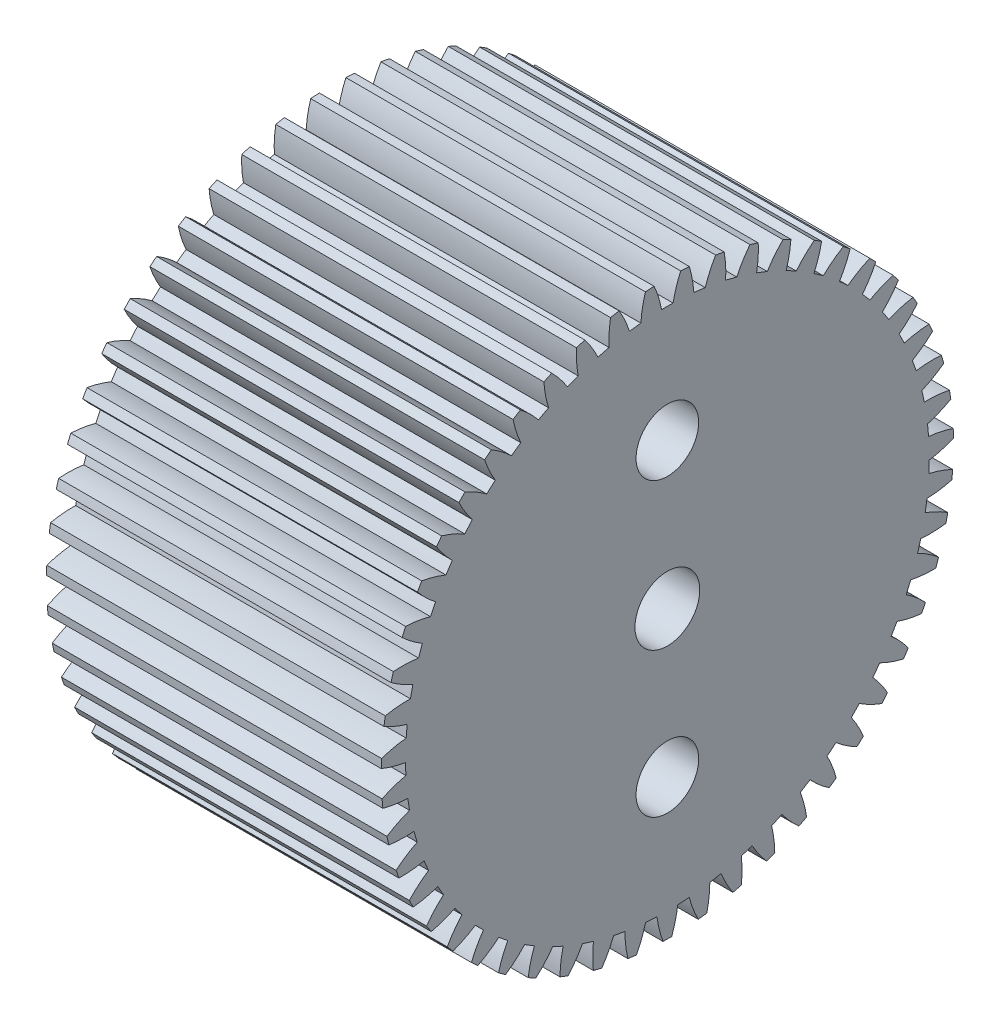
SolidWorks part; units mm, degrees
ref_plane "Plane1" through (0, 0, 0) normal (0, 0, 1) x (1, 0, 0)
ref_plane "Plane2" through (0, 0, 0) normal (0, 1, 0) x (1, 0, 0)
ref_plane "Plane3" through (0, 0, 0) normal (1, 0, 0) x (0, 0, -1)
sketch "HoldingSke" plane through (0, 0, 0) normal (0, 1, 0) x (1, 0, 0)
  line L0 (0, 0) -> (1.2586, -1.5543)
  line L1 (-15, 0) -> (100, 0) construction
  line L2 (0, 0) -> (-2.1039, 2.3779)
  line L3 (0, 0) -> (-11.863, 4.5341)
  line L4 (0, 0) -> (5.4348, 6.7114)
  line L5 (0, 0) -> (-46.8476, -17.4728)
  line L6 (0, 0) -> (-6.6317, -4.4744)
  line L7 (-2.1039, 2.3779) -> (8.6586, 51.2059)
  line L8 (-76.2, 54.61) -> (-75.7, 54.61)
  line L9 (-67.7845, 28.3722) -> (-49.3413, 33.142)
  line L10 (-76.2, 71.12) -> (104.1128, 71.12)
  line L11 (0, 0) -> (-8, 0)
  line L12 (-76.2, 101.6) -> (-76.181, 101.6)
  line L13 (24.9733, 27.94) -> (52.9518, 28.4284)
  line L14 (24.9733, 27.94) -> (24.9743, 27.94)
  line L15 (24.9733, 27.94) -> (100.4006, 29.5858)
  line L16 (-63.627, -0.5) -> (-12.827, -0.5)
  circle A0 centre (0, 0) radius 1.5
  circle A1 centre (0, 0) radius 12.124
  circle A2 centre (0, 0) radius 37.5
  circle A3 centre (0, 0) radius 1.5
  dimension "MHD" = 24.248
  dimension "Hub_dia" = 75
  dimension "Bore" = 3
  dimension "MBD" = 3
  dimension "Num_teeth" = 51
  dimension "Pitch" = 2
  dimension "Overall_len" = 50
  dimension "Show_teeth" = 51
  dimension "Thickness" = 8
  dimension "OAL" = 50.0001
  dimension "T_dim" = 0.5
  dimension "Ap" = 14.5
  dimension "H" = 19.05
  dimension "Pitch_radius" = 180.3128
  dimension "Width" = 8
  dimension "Backlash" = 0.019
  dimension "Addendum_fac" = 1
  dimension "Dedendum_fac" = 1.25
  dimension "Clearance_fac" = 0.25
  dimension "Dedendum_add" = 0.001
  dimension "Module" = 0.5
sketch "BasProSke" plane through (0, 0, 0) normal (0, 1, 0) x (1, 0, 0)
  line L0 (-10, 0) -> (60, 0) construction
  line L1 (0, 0) -> (0, 13.25)
  line L2 (0, 0) -> (8, 0)
  line L3 (8, 0) -> (8, 13.25)
  line L4 (8, 13.25) -> (0, 13.25)
  dimension "Thickness" = 8
  dimension "Diameter" = 26.5
revolve "Base-Revolve" add sketch "BasProSke" angle 360 about L0
sketch "TooCutSke" plane through (0, 0, 0) normal (1, 0, 0) x (0, 0, -1)
  line L1 (0, 0) -> (0, 107) construction
  line L2 (0, 0) -> (-0.4259, 12.7429) construction
  line L3 (0, 0) -> (-1.5692, 25.4415) construction
  line L4 (-0.4259, 12.7429) -> (-0.7846, 12.7208) construction
  arc A0 (0.2655, 12.1211) -> (-0.2655, 12.1211) centre (0, 0) ccw
  arc A1 (0.6267, 13.2606) -> (-0.6267, 13.2606) centre (0, 0) ccw
  circle A2 centre (0, 0) radius 12.75 construction
  circle A3 centre (0, 0) radius 12.3439 construction
  arc A4 (-0.2655, 12.1211) -> (-0.6267, 13.2606) centre (-5.2742, 11.1604) ccw
  arc A5 (0.6267, 13.2606) -> (0.2655, 12.1211) centre (5.2742, 11.1604) ccw
  dimension "Root_dia" = 24.248
  dimension "Overcut_dia" = 26.5508
  dimension "Pitch_dia" = 25.5
  dimension "Base_dia" = 24.6878
  dimension "Flank_rad" = 5.1
  dimension "Half_ang" = 3.529
  dimension "Half_CT" = 0.3594
extrude "ToothCut" cut sketch "TooCutSke" along normal through all
fillet "Breaks" [suppressed] radius 0.01
fillet "RootFillets" [suppressed] radius 0.126
pattern_circular "TeethCuts" count 51 every 7.059 about axis through (-10, 0, 0) along (1, 0, 0) of "ToothCut", "RootFillets", "Breaks"
sketch "HubNeaOneSke" plane through (0, 0, 0) normal (-1, 0, 0) x (0, 0, 1)
  circle A0 centre (0, 0) radius 12.124
  dimension "Diameter" = 24.248
extrude "HubNearOne" [suppressed] add sketch "HubNeaOneSke" along normal blind 42.0001
sketch "HubNeaBotSke" plane through (0, 0, 0) normal (-1, 0, 0) x (0, 0, 1)
  circle A0 centre (0, 0) radius 12.124
  dimension "Diameter" = 24.248
extrude "HubNearBoth" [suppressed] add sketch "HubNeaBotSke" along normal blind 21
ref_plane "FarPln" through (8, 0, 0) normal (1, 0, 0) x (0, 0, -1)
sketch "HubFarSke" plane through (8, 0, 0) normal (1, 0, 0) x (0, 0, -1)
  circle A0 centre (0, 0) radius 12.124
  dimension "Diameter" = 24.248
extrude "HubFar" [suppressed] add sketch "HubFarSke" along normal blind 21
sketch "BorSke" plane through (0, 0, 0) normal (1, 0, 0) x (0, 0, -1)
  circle A0 centre (0, 0) radius 1.5
  dimension "Diameter" = 3
extrude "Bore" cut sketch "BorSke" along normal mid plane 100.0001
sketch "KeySke" plane through (0, 0, 0) normal (1, 0, 0) x (0, 0, -1)
  line L0 (-0.6, 0) -> (-0.6, 2)
  line L1 (-0.6, 2) -> (0.6, 2)
  line L2 (0.6, 2) -> (0.6, 0)
  line L3 (0, 0) -> (0, 34) construction
  line L4 (-0.6, 0) -> (0.6, 0)
  dimension "Offset" = 2
  dimension "Width" = 1.2
extrude "Keyway" [suppressed] cut sketch "KeySke" along normal mid plane 100.0001
pattern_circular "Keyway2" [suppressed] count 2 every 90 about axis through (-10, 0, 0) along (1, 0, 0)
sketch "草圖1" plane through (8, 0, 0) normal (1, 0, 0) x (0, 0, -1)
  circle A0 centre (0, 0) radius 6.75 construction
  circle A1 centre (0, 6.75) radius 1.45
  circle A2 centre (0, -6.75) radius 1.45
  dimension "D1" = 13.5
  dimension "D2" = 2.9
extrude "除料-伸長1" cut sketch "草圖1" against normal up to next
sketch "草圖2" plane through (0, 0, 0) normal (-1, 0, 0) x (0, 0, 1)
  circle A0 centre (0, 6.75) radius 1.45 construction
  circle A1 centre (0, 6.75) radius 1.45
  circle A2 centre (0, 0) radius 1.5 construction
  circle A3 centre (0, 0) radius 1.5
  circle A4 centre (0, -6.75) radius 1.45 construction
  circle A5 centre (0, -6.75) radius 1.45
  arc A204 (12.1235, -0.1079) -> (13.2484, 0.2076) centre (11.3175, 4.928) ccw
  arc A205 (13.2484, 0.2076) -> (13.236, 0.6084) centre (0, 0) ccw
  arc A206 (13.236, 0.6084) -> (12.0939, 0.8541) centre (11.5994, -4.2219) ccw
  arc A207 (12.0939, 0.8541) -> (12.0449, 1.3827) centre (0, 0) ccw
  arc A208 (12.0449, 1.3827) -> (13.1224, 1.8341) centre (10.6262, 6.2814) ccw
  arc A209 (13.1224, 1.8341) -> (13.0609, 2.2303) centre (0, 0) ccw
  arc A210 (13.0609, 2.2303) -> (11.8973, 2.3338) centre (12.0303, -2.7645) ccw
  arc A211 (11.8973, 2.3338) -> (11.7837, 2.8524) centre (0, 0) ccw
  arc A212 (11.7837, 2.8524) -> (12.7976, 3.4328) centre (9.7737, 7.5396) ccw
  arc A213 (12.7976, 3.4328) -> (12.6879, 3.8184) centre (0, 0) ccw
  arc A214 (12.6879, 3.8184) -> (11.5203, 3.7781) centre (12.2789, -1.2651) ccw
  arc A215 (11.5203, 3.7781) -> (11.3438, 4.2789) centre (0, 0) ccw
  arc A216 (11.3438, 4.2789) -> (12.2787, 4.9795) centre (8.7731, 8.6836) ccw
  arc A217 (12.2787, 4.9795) -> (12.1225, 5.3487) centre (0, 0) ccw
  arc A218 (12.1225, 5.3487) -> (10.9687, 5.1652) centre (12.3413, 0.2534) ccw
  arc A219 (10.9687, 5.1652) -> (10.732, 5.6405) centre (0, 0) ccw
  arc A220 (10.732, 5.6405) -> (11.5738, 6.4506) centre (7.6395, 9.6959) ccw
  arc A221 (11.5738, 6.4506) -> (11.3733, 6.7979) centre (0, 0) ccw
  arc A222 (11.3733, 6.7979) -> (10.2508, 6.474) centre (12.2166, 1.7681) ccw
  arc A223 (10.2508, 6.474) -> (9.9575, 6.9166) centre (0, 0) ccw
  arc A224 (9.9575, 6.9166) -> (10.6933, 7.824) centre (6.3901, 10.5612) ccw
  arc A225 (10.6933, 7.824) -> (10.4517, 8.144) centre (0, 0) ccw
  arc A226 (10.4517, 8.144) -> (9.3775, 7.6846) centre (11.9067, 3.2559) ccw
  arc A227 (9.3775, 7.6846) -> (9.0321, 8.0878) centre (0, 0) ccw
  arc A228 (9.0321, 8.0878) -> (9.6508, 9.0788) centre (5.0438, 11.2664) ccw
  arc A229 (9.6508, 9.0788) -> (9.3717, 9.3666) centre (0, 0) ccw
  arc A230 (9.3717, 9.3666) -> (8.3621, 8.7788) centre (11.4164, 4.6945) ccw
  arc A231 (8.3621, 8.7788) -> (7.9698, 9.1364) centre (0, 0) ccw
  arc A232 (7.9698, 9.1364) -> (8.462, 10.196) centre (3.6211, 11.8008) ccw
  arc A233 (8.462, 10.196) -> (8.1496, 10.4473) centre (0, 0) ccw
  arc A234 (8.1496, 10.4473) -> (7.2199, 9.7398) centre (10.7529, 6.0618) ccw
  arc A235 (7.2199, 9.7398) -> (6.7866, 10.0466) centre (0, 0) ccw
  arc A236 (6.7866, 10.0466) -> (7.1449, 11.1586) centre (2.1434, 12.1564) ccw
  arc A237 (7.1449, 11.1586) -> (6.804, 11.3696) centre (0, 0) ccw
  arc A238 (6.804, 11.3696) -> (5.9683, 10.5532) centre (9.9265, 7.3373) ccw
  arc A239 (5.9683, 10.5532) -> (5.5005, 10.8044) centre (0, 0) ccw
  arc A240 (5.5005, 10.8044) -> (5.7195, 11.952) centre (0.6333, 12.3276) ccw
  arc A241 (5.7195, 11.952) -> (5.3552, 12.1196) centre (0, 0) ccw
  arc A242 (5.3552, 12.1196) -> (4.6262, 11.2067) centre (8.9496, 8.5015) ccw
  arc A243 (4.6262, 11.2067) -> (4.1311, 11.3985) centre (0, 0) ccw
  arc A244 (4.1311, 11.3985) -> (4.2074, 12.5643) centre (-0.8864, 12.312) ccw
  arc A245 (4.2074, 12.5643) -> (3.8253, 12.6858) centre (0, 0) ccw
  arc A246 (3.8253, 12.6858) -> (3.2139, 11.6903) centre (7.837, 9.5369) ccw
  arc A247 (3.2139, 11.6903) -> (2.6991, 11.8197) centre (0, 0) ccw
  arc A248 (2.6991, 11.8197) -> (2.6315, 12.9861) centre (-2.3927, 12.1098) ccw
  arc A249 (2.6315, 12.9861) -> (2.2373, 13.0597) centre (0, 0) ccw
  arc A250 (2.2373, 13.0597) -> (1.753, 11.9966) centre (6.6057, 10.4277) ccw
  arc A251 (1.753, 11.9966) -> (1.2261, 12.0618) centre (0, 0) ccw
  arc A252 (1.2261, 12.0618) -> (1.0157, 13.211) centre (-3.8627, 11.7239) ccw
  arc A253 (1.0157, 13.211) -> (0.6155, 13.2357) centre (0, 0) ccw
  arc A254 (0.6155, 13.2357) -> (0.2655, 12.1211) centre (5.2742, 11.1604) ccw
  arc A255 (0.2655, 12.1211) -> (-0.2655, 12.1211) centre (0, 0) ccw
  arc A256 (-0.2655, 12.1211) -> (-0.6155, 13.2357) centre (-5.2742, 11.1604) ccw
  arc A257 (-0.6155, 13.2357) -> (-1.0157, 13.211) centre (0, 0) ccw
  arc A258 (-1.0157, 13.211) -> (-1.2261, 12.0618) centre (3.8627, 11.7239) ccw
  arc A259 (-1.2261, 12.0618) -> (-1.753, 11.9966) centre (0, 0) ccw
  arc A260 (-1.753, 11.9966) -> (-2.2373, 13.0597) centre (-6.6057, 10.4277) ccw
  arc A261 (-2.2373, 13.0597) -> (-2.6315, 12.9861) centre (0, 0) ccw
  arc A262 (-2.6315, 12.9861) -> (-2.6991, 11.8197) centre (2.3927, 12.1098) ccw
  arc A263 (-2.6991, 11.8197) -> (-3.2139, 11.6903) centre (0, 0) ccw
  arc A264 (-3.2139, 11.6903) -> (-3.8253, 12.6858) centre (-7.837, 9.5369) ccw
  arc A265 (-3.8253, 12.6858) -> (-4.2074, 12.5643) centre (0, 0) ccw
  arc A266 (-4.2074, 12.5643) -> (-4.1311, 11.3985) centre (0.8864, 12.312) ccw
  arc A267 (-4.1311, 11.3985) -> (-4.6262, 11.2067) centre (0, 0) ccw
  arc A268 (-4.6262, 11.2067) -> (-5.3552, 12.1196) centre (-8.9496, 8.5015) ccw
  arc A269 (-5.3552, 12.1196) -> (-5.7195, 11.952) centre (0, 0) ccw
  arc A270 (-5.7195, 11.952) -> (-5.5005, 10.8044) centre (-0.6333, 12.3276) ccw
  arc A271 (-5.5005, 10.8044) -> (-5.9683, 10.5532) centre (0, 0) ccw
  arc A272 (-5.9683, 10.5532) -> (-6.804, 11.3696) centre (-9.9265, 7.3373) ccw
  arc A273 (-6.804, 11.3696) -> (-7.1449, 11.1586) centre (0, 0) ccw
  arc A274 (-7.1449, 11.1586) -> (-6.7866, 10.0466) centre (-2.1434, 12.1564) ccw
  arc A275 (-6.7866, 10.0466) -> (-7.2199, 9.7398) centre (0, 0) ccw
  arc A276 (-7.2199, 9.7398) -> (-8.1496, 10.4473) centre (-10.7529, 6.0618) ccw
  arc A277 (-8.1496, 10.4473) -> (-8.462, 10.196) centre (0, 0) ccw
  arc A278 (-8.462, 10.196) -> (-7.9698, 9.1364) centre (-3.6211, 11.8008) ccw
  arc A279 (-7.9698, 9.1364) -> (-8.3621, 8.7788) centre (0, 0) ccw
  arc A280 (-8.3621, 8.7788) -> (-9.3717, 9.3666) centre (-11.4164, 4.6945) ccw
  arc A281 (-9.3717, 9.3666) -> (-9.6508, 9.0788) centre (0, 0) ccw
  arc A282 (-9.6508, 9.0788) -> (-9.0321, 8.0878) centre (-5.0438, 11.2664) ccw
  arc A283 (-9.0321, 8.0878) -> (-9.3775, 7.6846) centre (0, 0) ccw
  arc A284 (-9.3775, 7.6846) -> (-10.4517, 8.144) centre (-11.9067, 3.2559) ccw
  arc A285 (-10.4517, 8.144) -> (-10.6933, 7.824) centre (0, 0) ccw
  arc A286 (-10.6933, 7.824) -> (-9.9575, 6.9166) centre (-6.3901, 10.5612) ccw
  arc A287 (-9.9575, 6.9166) -> (-10.2508, 6.474) centre (0, 0) ccw
  arc A288 (-10.2508, 6.474) -> (-11.3733, 6.7979) centre (-12.2166, 1.7681) ccw
  arc A289 (-11.3733, 6.7979) -> (-11.5738, 6.4506) centre (0, 0) ccw
  arc A290 (-11.5738, 6.4506) -> (-10.732, 5.6405) centre (-7.6395, 9.6959) ccw
  arc A291 (-10.732, 5.6405) -> (-10.9687, 5.1652) centre (0, 0) ccw
  arc A292 (-10.9687, 5.1652) -> (-12.1225, 5.3487) centre (-12.3413, 0.2534) ccw
  arc A293 (-12.1225, 5.3487) -> (-12.2787, 4.9795) centre (0, 0) ccw
  arc A294 (-12.2787, 4.9795) -> (-11.3438, 4.2789) centre (-8.7731, 8.6836) ccw
  arc A295 (-11.3438, 4.2789) -> (-11.5203, 3.7781) centre (0, 0) ccw
  arc A296 (-11.5203, 3.7781) -> (-12.6879, 3.8184) centre (-12.2789, -1.2651) ccw
  arc A297 (-12.6879, 3.8184) -> (-12.7976, 3.4328) centre (0, 0) ccw
  arc A298 (-12.7976, 3.4328) -> (-11.7837, 2.8524) centre (-9.7737, 7.5396) ccw
  arc A299 (-11.7837, 2.8524) -> (-11.8973, 2.3338) centre (0, 0) ccw
  arc A300 (-11.8973, 2.3338) -> (-13.0609, 2.2303) centre (-12.0303, -2.7645) ccw
  arc A301 (-13.0609, 2.2303) -> (-13.1224, 1.8341) centre (0, 0) ccw
  arc A302 (-13.1224, 1.8341) -> (-12.0449, 1.3827) centre (-10.6262, 6.2814) ccw
  arc A303 (-12.0449, 1.3827) -> (-12.0939, 0.8541) centre (0, 0) ccw
  arc A304 (-12.0939, 0.8541) -> (-13.236, 0.6084) centre (-11.5994, -4.2219) ccw
  arc A305 (-13.236, 0.6084) -> (-13.2484, 0.2076) centre (0, 0) ccw
  arc A306 (-13.2484, 0.2076) -> (-12.1235, -0.1079) centre (-11.3175, 4.928) ccw
  arc A307 (-12.1235, -0.1079) -> (-12.1072, -0.6386) centre (0, 0) ccw
  arc A308 (-12.1072, -0.6386) -> (-13.2105, -1.0228) centre (-10.9927, -5.6153) ccw
  arc A309 (-13.2105, -1.0228) -> (-13.1735, -1.422) centre (0, 0) ccw
  arc A310 (-13.1735, -1.422) -> (-12.0184, -1.597) centre (-11.8373, 3.4998) ccw
  arc A311 (-12.0184, -1.597) -> (-11.9369, -2.1216) centre (0, 0) ccw
  arc A312 (-11.9369, -2.1216) -> (-12.9846, -2.6385) centre (-10.2193, -6.9237) ccw
  arc A313 (-12.9846, -2.6385) -> (-12.8989, -3.0301) centre (0, 0) ccw
  arc A314 (-12.8989, -3.0301) -> (-11.731, -3.0618) centre (-12.1777, 2.0186) ccw
  arc A315 (-11.731, -3.0618) -> (-11.5857, -3.5724) centre (0, 0) ccw
  arc A316 (-11.5857, -3.5724) -> (-12.562, -4.2141) centre (-9.291, -8.127) ccw
  arc A317 (-12.562, -4.2141) -> (-12.4287, -4.5923) centre (0, 0) ccw
  arc A318 (-12.4287, -4.5923) -> (-11.2659, -4.4802) centre (-12.3335, 0.5068) ccw
  arc A319 (-11.2659, -4.4802) -> (-11.0589, -4.9691) centre (0, 0) ccw
  arc A320 (-11.0589, -4.9691) -> (-11.9489, -5.7259) centre (-8.2219, -9.2072) ccw
  arc A321 (-11.9489, -5.7259) -> (-11.7702, -6.0848) centre (0, 0) ccw
  arc A322 (-11.7702, -6.0848) -> (-10.6299, -5.8307) centre (-12.3023, -1.0126) ccw
  arc A323 (-10.6299, -5.8307) -> (-10.3644, -6.2904) centre (0, 0) ccw
  arc A324 (-10.3644, -6.2904) -> (-11.1547, -7.1509) centre (-7.0281, -10.1478) ccw
  arc A325 (-11.1547, -7.1509) -> (-10.9332, -7.4851) centre (0, 0) ccw
  arc A326 (-10.9332, -7.4851) -> (-9.8328, -7.0928) centre (-12.0846, -2.5168) ccw
  arc A327 (-9.8328, -7.0928) -> (-9.5129, -7.5164) centre (0, 0) ccw
  arc A328 (-9.5129, -7.5164) -> (-10.1914, -8.4675) centre (-5.7278, -10.9345) ccw
  arc A329 (-10.1914, -8.4675) -> (-9.9305, -8.7719) centre (0, 0) ccw
  arc A330 (-9.9305, -8.7719) -> (-8.8867, -8.2473) centre (-11.6837, -3.9828) ccw
  arc A331 (-8.8867, -8.2473) -> (-8.5171, -8.6285) centre (0, 0) ccw
  arc A332 (-8.5171, -8.6285) -> (-9.0736, -9.6557) centre (-4.3407, -11.5555) ccw
  arc A333 (-9.0736, -9.6557) -> (-8.7773, -9.9258) centre (0, 0) ccw
  arc A334 (-8.7773, -9.9258) -> (-7.8058, -9.2769) centre (-11.1057, -5.3884) ccw
  arc A335 (-7.8058, -9.2769) -> (-7.3922, -9.6097) centre (0, 0) ccw
  arc A336 (-7.3922, -9.6097) -> (-7.8183, -10.6975) centre (-2.8877, -12.0014) ccw
  arc A337 (-7.8183, -10.6975) -> (-7.491, -10.9292) centre (0, 0) ccw
  arc A338 (-7.491, -10.9292) -> (-6.6066, -10.1658) centre (-10.3594, -6.7123) ccw
  arc A339 (-6.6066, -10.1658) -> (-6.1552, -10.4453) centre (0, 0) ccw
  arc A340 (-6.1552, -10.4453) -> (-6.4444, -11.5772) centre (-1.391, -12.2653) ccw
  arc A341 (-6.4444, -11.5772) -> (-6.0911, -11.7669) centre (0, 0) ccw
  arc A342 (-6.0911, -11.7669) -> (-5.3073, -10.9006) centre (-9.456, -7.9345) ccw
  arc A343 (-5.3073, -10.9006) -> (-4.825, -11.1225) centre (0, 0) ccw
  arc A344 (-4.825, -11.1225) -> (-4.9728, -12.2814) centre (0.1268, -12.3432) ccw
  arc A345 (-4.9728, -12.2814) -> (-4.599, -12.4263) centre (0, 0) ccw
  arc A346 (-4.599, -12.4263) -> (-3.9275, -11.4702) centre (-8.4093, -9.0363) ccw
  arc A347 (-3.9275, -11.4702) -> (-3.4216, -11.6312) centre (0, 0) ccw
  arc A348 (-3.4216, -11.6312) -> (-3.4259, -12.7994) centre (1.6427, -12.2341) ccw
  arc A349 (-3.4259, -12.7994) -> (-3.0371, -12.8972) centre (0, 0) ccw
  arc A350 (-3.0371, -12.8972) -> (-2.4882, -11.8659) centre (-7.2351, -10.0013) ccw
  arc A351 (-2.4882, -11.8659) -> (-1.9663, -11.9635) centre (0, 0) ccw
  arc A352 (-1.9663, -11.9635) -> (-1.827, -13.1234) centre (3.1336, -11.9395) ccw
  arc A353 (-1.827, -13.1234) -> (-1.4291, -13.1727) centre (0, 0) ccw
  arc A354 (-1.4291, -13.1727) -> (-1.0111, -12.0818) centre (-5.9512, -10.8146) ccw
  arc A355 (-1.0111, -12.0818) -> (-0.4812, -12.1144) centre (0, 0) ccw
  arc A356 (-0.4812, -12.1144) -> (-0.2005, -13.2485) centre (4.5771, -11.4639) ccw
  arc A357 (-0.2005, -13.2485) -> (0.2005, -13.2485) centre (0, 0) ccw
  arc A358 (0.2005, -13.2485) -> (0.4812, -12.1144) centre (-4.5771, -11.4639) ccw
  arc A359 (0.4812, -12.1144) -> (1.0111, -12.0818) centre (0, 0) ccw
  arc A360 (1.0111, -12.0818) -> (1.4291, -13.1727) centre (5.9512, -10.8146) ccw
  arc A361 (1.4291, -13.1727) -> (1.827, -13.1234) centre (0, 0) ccw
  arc A362 (1.827, -13.1234) -> (1.9663, -11.9635) centre (-3.1336, -11.9395) ccw
  arc A363 (1.9663, -11.9635) -> (2.4882, -11.8659) centre (0, 0) ccw
  arc A364 (2.4882, -11.8659) -> (3.0371, -12.8972) centre (7.2351, -10.0013) ccw
  arc A365 (3.0371, -12.8972) -> (3.4259, -12.7994) centre (0, 0) ccw
  arc A366 (3.4259, -12.7994) -> (3.4216, -11.6312) centre (-1.6427, -12.2341) ccw
  arc A367 (3.4216, -11.6312) -> (3.9275, -11.4702) centre (0, 0) ccw
  arc A368 (3.9275, -11.4702) -> (4.599, -12.4263) centre (8.4093, -9.0363) ccw
  arc A369 (4.599, -12.4263) -> (4.9728, -12.2814) centre (0, 0) ccw
  arc A370 (4.9728, -12.2814) -> (4.825, -11.1225) centre (-0.1268, -12.3432) ccw
  arc A371 (4.825, -11.1225) -> (5.3073, -10.9006) centre (0, 0) ccw
  arc A372 (5.3073, -10.9006) -> (6.0911, -11.7669) centre (9.456, -7.9345) ccw
  arc A373 (6.0911, -11.7669) -> (6.4444, -11.5772) centre (0, 0) ccw
  arc A374 (6.4444, -11.5772) -> (6.1552, -10.4453) centre (1.391, -12.2653) ccw
  arc A375 (6.1552, -10.4453) -> (6.6066, -10.1658) centre (0, 0) ccw
  arc A376 (6.6066, -10.1658) -> (7.491, -10.9292) centre (10.3594, -6.7123) ccw
  arc A377 (7.491, -10.9292) -> (7.8183, -10.6975) centre (0, 0) ccw
  arc A378 (7.8183, -10.6975) -> (7.3922, -9.6097) centre (2.8877, -12.0014) ccw
  arc A379 (7.3922, -9.6097) -> (7.8058, -9.2769) centre (0, 0) ccw
  arc A380 (7.8058, -9.2769) -> (8.7773, -9.9258) centre (11.1057, -5.3884) ccw
  arc A381 (8.7773, -9.9258) -> (9.0736, -9.6557) centre (0, 0) ccw
  arc A382 (9.0736, -9.6557) -> (8.5171, -8.6285) centre (4.3407, -11.5555) ccw
  arc A383 (8.5171, -8.6285) -> (8.8867, -8.2473) centre (0, 0) ccw
  arc A384 (8.8867, -8.2473) -> (9.9305, -8.7719) centre (11.6837, -3.9828) ccw
  arc A385 (9.9305, -8.7719) -> (10.1914, -8.4675) centre (0, 0) ccw
  arc A386 (10.1914, -8.4675) -> (9.5129, -7.5164) centre (5.7278, -10.9345) ccw
  arc A387 (9.5129, -7.5164) -> (9.8328, -7.0928) centre (0, 0) ccw
  arc A388 (9.8328, -7.0928) -> (10.9332, -7.4851) centre (12.0846, -2.5168) ccw
  arc A389 (10.9332, -7.4851) -> (11.1547, -7.1509) centre (0, 0) ccw
  arc A390 (11.1547, -7.1509) -> (10.3644, -6.2904) centre (7.0281, -10.1478) ccw
  arc A391 (10.3644, -6.2904) -> (10.6299, -5.8307) centre (0, 0) ccw
  arc A392 (10.6299, -5.8307) -> (11.7702, -6.0848) centre (12.3023, -1.0126) ccw
  arc A393 (11.7702, -6.0848) -> (11.9489, -5.7259) centre (0, 0) ccw
  arc A394 (11.9489, -5.7259) -> (11.0589, -4.9691) centre (8.2219, -9.2072) ccw
  arc A395 (11.0589, -4.9691) -> (11.2659, -4.4802) centre (0, 0) ccw
  arc A396 (11.2659, -4.4802) -> (12.4287, -4.5923) centre (12.3335, 0.5068) ccw
  arc A397 (12.4287, -4.5923) -> (12.562, -4.2141) centre (0, 0) ccw
  arc A398 (12.562, -4.2141) -> (11.5857, -3.5724) centre (9.291, -8.127) ccw
  arc A399 (11.5857, -3.5724) -> (11.731, -3.0618) centre (0, 0) ccw
  arc A400 (11.731, -3.0618) -> (12.8989, -3.0301) centre (12.1777, 2.0186) ccw
  arc A401 (12.8989, -3.0301) -> (12.9846, -2.6385) centre (0, 0) ccw
  arc A402 (12.9846, -2.6385) -> (11.9369, -2.1216) centre (10.2193, -6.9237) ccw
  arc A403 (11.9369, -2.1216) -> (12.0184, -1.597) centre (0, 0) ccw
  arc A404 (12.0184, -1.597) -> (13.1735, -1.422) centre (11.8373, 3.4998) ccw
  arc A405 (13.1735, -1.422) -> (13.2105, -1.0228) centre (0, 0) ccw
  arc A406 (13.2105, -1.0228) -> (12.1072, -0.6386) centre (10.9927, -5.6153) ccw
  arc A407 (12.1072, -0.6386) -> (12.1235, -0.1079) centre (0, 0) ccw
  arc A408 (12.1235, -0.1079) -> (13.2484, 0.2076) centre (11.3175, 4.928) ccw
  arc A409 (13.2484, 0.2076) -> (13.236, 0.6084) centre (0, 0) ccw
  arc A410 (13.236, 0.6084) -> (12.0939, 0.8541) centre (11.5994, -4.2219) ccw
  arc A411 (12.0939, 0.8541) -> (12.0449, 1.3827) centre (0, 0) ccw
  arc A412 (12.0449, 1.3827) -> (13.1224, 1.8341) centre (10.6262, 6.2814) ccw
  arc A413 (13.1224, 1.8341) -> (13.0609, 2.2303) centre (0, 0) ccw
  arc A414 (13.0609, 2.2303) -> (11.8973, 2.3338) centre (12.0303, -2.7645) ccw
  arc A415 (11.8973, 2.3338) -> (11.7837, 2.8524) centre (0, 0) ccw
  arc A416 (11.7837, 2.8524) -> (12.7976, 3.4328) centre (9.7737, 7.5396) ccw
  arc A417 (12.7976, 3.4328) -> (12.6879, 3.8184) centre (0, 0) ccw
  arc A418 (12.6879, 3.8184) -> (11.5203, 3.7781) centre (12.2789, -1.2651) ccw
  arc A419 (11.5203, 3.7781) -> (11.3438, 4.2789) centre (0, 0) ccw
  arc A420 (11.3438, 4.2789) -> (12.2787, 4.9795) centre (8.7731, 8.6836) ccw
  arc A421 (12.2787, 4.9795) -> (12.1225, 5.3487) centre (0, 0) ccw
  arc A422 (12.1225, 5.3487) -> (10.9687, 5.1652) centre (12.3413, 0.2534) ccw
  arc A423 (10.9687, 5.1652) -> (10.732, 5.6405) centre (0, 0) ccw
  arc A424 (10.732, 5.6405) -> (11.5738, 6.4506) centre (7.6395, 9.6959) ccw
  arc A425 (11.5738, 6.4506) -> (11.3733, 6.7979) centre (0, 0) ccw
  arc A426 (11.3733, 6.7979) -> (10.2508, 6.474) centre (12.2166, 1.7681) ccw
  arc A427 (10.2508, 6.474) -> (9.9575, 6.9166) centre (0, 0) ccw
  arc A428 (9.9575, 6.9166) -> (10.6933, 7.824) centre (6.3901, 10.5612) ccw
  arc A429 (10.6933, 7.824) -> (10.4517, 8.144) centre (0, 0) ccw
  arc A430 (10.4517, 8.144) -> (9.3775, 7.6846) centre (11.9067, 3.2559) ccw
  arc A431 (9.3775, 7.6846) -> (9.0321, 8.0878) centre (0, 0) ccw
  arc A432 (9.0321, 8.0878) -> (9.6508, 9.0788) centre (5.0438, 11.2664) ccw
  arc A433 (9.6508, 9.0788) -> (9.3717, 9.3666) centre (0, 0) ccw
  arc A434 (9.3717, 9.3666) -> (8.3621, 8.7788) centre (11.4164, 4.6945) ccw
  arc A435 (8.3621, 8.7788) -> (7.9698, 9.1364) centre (0, 0) ccw
  arc A436 (7.9698, 9.1364) -> (8.462, 10.196) centre (3.6211, 11.8008) ccw
  arc A437 (8.462, 10.196) -> (8.1496, 10.4473) centre (0, 0) ccw
  arc A438 (8.1496, 10.4473) -> (7.2199, 9.7398) centre (10.7529, 6.0618) ccw
  arc A439 (7.2199, 9.7398) -> (6.7866, 10.0466) centre (0, 0) ccw
  arc A440 (6.7866, 10.0466) -> (7.1449, 11.1586) centre (2.1434, 12.1564) ccw
  arc A441 (7.1449, 11.1586) -> (6.804, 11.3696) centre (0, 0) ccw
  arc A442 (6.804, 11.3696) -> (5.9683, 10.5532) centre (9.9265, 7.3373) ccw
  arc A443 (5.9683, 10.5532) -> (5.5005, 10.8044) centre (0, 0) ccw
  arc A444 (5.5005, 10.8044) -> (5.7195, 11.952) centre (0.6333, 12.3276) ccw
  arc A445 (5.7195, 11.952) -> (5.3552, 12.1196) centre (0, 0) ccw
  arc A446 (5.3552, 12.1196) -> (4.6262, 11.2067) centre (8.9496, 8.5015) ccw
  arc A447 (4.6262, 11.2067) -> (4.1311, 11.3985) centre (0, 0) ccw
  arc A448 (4.1311, 11.3985) -> (4.2074, 12.5643) centre (-0.8864, 12.312) ccw
  arc A449 (4.2074, 12.5643) -> (3.8253, 12.6858) centre (0, 0) ccw
  arc A450 (3.8253, 12.6858) -> (3.2139, 11.6903) centre (7.837, 9.5369) ccw
  arc A451 (3.2139, 11.6903) -> (2.6991, 11.8197) centre (0, 0) ccw
  arc A452 (2.6991, 11.8197) -> (2.6315, 12.9861) centre (-2.3927, 12.1098) ccw
  arc A453 (2.6315, 12.9861) -> (2.2373, 13.0597) centre (0, 0) ccw
  arc A454 (2.2373, 13.0597) -> (1.753, 11.9966) centre (6.6057, 10.4277) ccw
  arc A455 (1.753, 11.9966) -> (1.2261, 12.0618) centre (0, 0) ccw
  arc A456 (1.2261, 12.0618) -> (1.0157, 13.211) centre (-3.8627, 11.7239) ccw
  arc A457 (1.0157, 13.211) -> (0.6155, 13.2357) centre (0, 0) ccw
  arc A458 (0.6155, 13.2357) -> (0.2655, 12.1211) centre (5.2742, 11.1604) ccw
  arc A459 (0.2655, 12.1211) -> (-0.2655, 12.1211) centre (0, 0) ccw
  arc A460 (-0.2655, 12.1211) -> (-0.6155, 13.2357) centre (-5.2742, 11.1604) ccw
  arc A461 (-0.6155, 13.2357) -> (-1.0157, 13.211) centre (0, 0) ccw
  arc A462 (-1.0157, 13.211) -> (-1.2261, 12.0618) centre (3.8627, 11.7239) ccw
  arc A463 (-1.2261, 12.0618) -> (-1.753, 11.9966) centre (0, 0) ccw
  arc A464 (-1.753, 11.9966) -> (-2.2373, 13.0597) centre (-6.6057, 10.4277) ccw
  arc A465 (-2.2373, 13.0597) -> (-2.6315, 12.9861) centre (0, 0) ccw
  arc A466 (-2.6315, 12.9861) -> (-2.6991, 11.8197) centre (2.3927, 12.1098) ccw
  arc A467 (-2.6991, 11.8197) -> (-3.2139, 11.6903) centre (0, 0) ccw
  arc A468 (-3.2139, 11.6903) -> (-3.8253, 12.6858) centre (-7.837, 9.5369) ccw
  arc A469 (-3.8253, 12.6858) -> (-4.2074, 12.5643) centre (0, 0) ccw
  arc A470 (-4.2074, 12.5643) -> (-4.1311, 11.3985) centre (0.8864, 12.312) ccw
  arc A471 (-4.1311, 11.3985) -> (-4.6262, 11.2067) centre (0, 0) ccw
  arc A472 (-4.6262, 11.2067) -> (-5.3552, 12.1196) centre (-8.9496, 8.5015) ccw
  arc A473 (-5.3552, 12.1196) -> (-5.7195, 11.952) centre (0, 0) ccw
  arc A474 (-5.7195, 11.952) -> (-5.5005, 10.8044) centre (-0.6333, 12.3276) ccw
  arc A475 (-5.5005, 10.8044) -> (-5.9683, 10.5532) centre (0, 0) ccw
  arc A476 (-5.9683, 10.5532) -> (-6.804, 11.3696) centre (-9.9265, 7.3373) ccw
  arc A477 (-6.804, 11.3696) -> (-7.1449, 11.1586) centre (0, 0) ccw
  arc A478 (-7.1449, 11.1586) -> (-6.7866, 10.0466) centre (-2.1434, 12.1564) ccw
  arc A479 (-6.7866, 10.0466) -> (-7.2199, 9.7398) centre (0, 0) ccw
  arc A480 (-7.2199, 9.7398) -> (-8.1496, 10.4473) centre (-10.7529, 6.0618) ccw
  arc A481 (-8.1496, 10.4473) -> (-8.462, 10.196) centre (0, 0) ccw
  arc A482 (-8.462, 10.196) -> (-7.9698, 9.1364) centre (-3.6211, 11.8008) ccw
  arc A483 (-7.9698, 9.1364) -> (-8.3621, 8.7788) centre (0, 0) ccw
  arc A484 (-8.3621, 8.7788) -> (-9.3717, 9.3666) centre (-11.4164, 4.6945) ccw
  arc A485 (-9.3717, 9.3666) -> (-9.6508, 9.0788) centre (0, 0) ccw
  arc A486 (-9.6508, 9.0788) -> (-9.0321, 8.0878) centre (-5.0438, 11.2664) ccw
  arc A487 (-9.0321, 8.0878) -> (-9.3775, 7.6846) centre (0, 0) ccw
  arc A488 (-9.3775, 7.6846) -> (-10.4517, 8.144) centre (-11.9067, 3.2559) ccw
  arc A489 (-10.4517, 8.144) -> (-10.6933, 7.824) centre (0, 0) ccw
  arc A490 (-10.6933, 7.824) -> (-9.9575, 6.9166) centre (-6.3901, 10.5612) ccw
  arc A491 (-9.9575, 6.9166) -> (-10.2508, 6.474) centre (0, 0) ccw
  arc A492 (-10.2508, 6.474) -> (-11.3733, 6.7979) centre (-12.2166, 1.7681) ccw
  arc A493 (-11.3733, 6.7979) -> (-11.5738, 6.4506) centre (0, 0) ccw
  arc A494 (-11.5738, 6.4506) -> (-10.732, 5.6405) centre (-7.6395, 9.6959) ccw
  arc A495 (-10.732, 5.6405) -> (-10.9687, 5.1652) centre (0, 0) ccw
  arc A496 (-10.9687, 5.1652) -> (-12.1225, 5.3487) centre (-12.3413, 0.2534) ccw
  arc A497 (-12.1225, 5.3487) -> (-12.2787, 4.9795) centre (0, 0) ccw
  arc A498 (-12.2787, 4.9795) -> (-11.3438, 4.2789) centre (-8.7731, 8.6836) ccw
  arc A499 (-11.3438, 4.2789) -> (-11.5203, 3.7781) centre (0, 0) ccw
  arc A500 (-11.5203, 3.7781) -> (-12.6879, 3.8184) centre (-12.2789, -1.2651) ccw
  arc A501 (-12.6879, 3.8184) -> (-12.7976, 3.4328) centre (0, 0) ccw
  arc A502 (-12.7976, 3.4328) -> (-11.7837, 2.8524) centre (-9.7737, 7.5396) ccw
  arc A503 (-11.7837, 2.8524) -> (-11.8973, 2.3338) centre (0, 0) ccw
  arc A504 (-11.8973, 2.3338) -> (-13.0609, 2.2303) centre (-12.0303, -2.7645) ccw
  arc A505 (-13.0609, 2.2303) -> (-13.1224, 1.8341) centre (0, 0) ccw
  arc A506 (-13.1224, 1.8341) -> (-12.0449, 1.3827) centre (-10.6262, 6.2814) ccw
  arc A507 (-12.0449, 1.3827) -> (-12.0939, 0.8541) centre (0, 0) ccw
  arc A508 (-12.0939, 0.8541) -> (-13.236, 0.6084) centre (-11.5994, -4.2219) ccw
  arc A509 (-13.236, 0.6084) -> (-13.2484, 0.2076) centre (0, 0) ccw
  arc A510 (-13.2484, 0.2076) -> (-12.1235, -0.1079) centre (-11.3175, 4.928) ccw
  arc A511 (-12.1235, -0.1079) -> (-12.1072, -0.6386) centre (0, 0) ccw
  arc A512 (-12.1072, -0.6386) -> (-13.2105, -1.0228) centre (-10.9927, -5.6153) ccw
  arc A513 (-13.2105, -1.0228) -> (-13.1735, -1.422) centre (0, 0) ccw
  arc A514 (-13.1735, -1.422) -> (-12.0184, -1.597) centre (-11.8373, 3.4998) ccw
  arc A515 (-12.0184, -1.597) -> (-11.9369, -2.1216) centre (0, 0) ccw
  arc A516 (-11.9369, -2.1216) -> (-12.9846, -2.6385) centre (-10.2193, -6.9237) ccw
  arc A517 (-12.9846, -2.6385) -> (-12.8989, -3.0301) centre (0, 0) ccw
  arc A518 (-12.8989, -3.0301) -> (-11.731, -3.0618) centre (-12.1777, 2.0186) ccw
  arc A519 (-11.731, -3.0618) -> (-11.5857, -3.5724) centre (0, 0) ccw
  arc A520 (-11.5857, -3.5724) -> (-12.562, -4.2141) centre (-9.291, -8.127) ccw
  arc A521 (-12.562, -4.2141) -> (-12.4287, -4.5923) centre (0, 0) ccw
  arc A522 (-12.4287, -4.5923) -> (-11.2659, -4.4802) centre (-12.3335, 0.5068) ccw
  arc A523 (-11.2659, -4.4802) -> (-11.0589, -4.9691) centre (0, 0) ccw
  arc A524 (-11.0589, -4.9691) -> (-11.9489, -5.7259) centre (-8.2219, -9.2072) ccw
  arc A525 (-11.9489, -5.7259) -> (-11.7702, -6.0848) centre (0, 0) ccw
  arc A526 (-11.7702, -6.0848) -> (-10.6299, -5.8307) centre (-12.3023, -1.0126) ccw
  arc A527 (-10.6299, -5.8307) -> (-10.3644, -6.2904) centre (0, 0) ccw
  arc A528 (-10.3644, -6.2904) -> (-11.1547, -7.1509) centre (-7.0281, -10.1478) ccw
  arc A529 (-11.1547, -7.1509) -> (-10.9332, -7.4851) centre (0, 0) ccw
  arc A530 (-10.9332, -7.4851) -> (-9.8328, -7.0928) centre (-12.0846, -2.5168) ccw
  arc A531 (-9.8328, -7.0928) -> (-9.5129, -7.5164) centre (0, 0) ccw
  arc A532 (-9.5129, -7.5164) -> (-10.1914, -8.4675) centre (-5.7278, -10.9345) ccw
  arc A533 (-10.1914, -8.4675) -> (-9.9305, -8.7719) centre (0, 0) ccw
  arc A534 (-9.9305, -8.7719) -> (-8.8867, -8.2473) centre (-11.6837, -3.9828) ccw
  arc A535 (-8.8867, -8.2473) -> (-8.5171, -8.6285) centre (0, 0) ccw
  arc A536 (-8.5171, -8.6285) -> (-9.0736, -9.6557) centre (-4.3407, -11.5555) ccw
  arc A537 (-9.0736, -9.6557) -> (-8.7773, -9.9258) centre (0, 0) ccw
  arc A538 (-8.7773, -9.9258) -> (-7.8058, -9.2769) centre (-11.1057, -5.3884) ccw
  arc A539 (-7.8058, -9.2769) -> (-7.3922, -9.6097) centre (0, 0) ccw
  arc A540 (-7.3922, -9.6097) -> (-7.8183, -10.6975) centre (-2.8877, -12.0014) ccw
  arc A541 (-7.8183, -10.6975) -> (-7.491, -10.9292) centre (0, 0) ccw
  arc A542 (-7.491, -10.9292) -> (-6.6066, -10.1658) centre (-10.3594, -6.7123) ccw
  arc A543 (-6.6066, -10.1658) -> (-6.1552, -10.4453) centre (0, 0) ccw
  arc A544 (-6.1552, -10.4453) -> (-6.4444, -11.5772) centre (-1.391, -12.2653) ccw
  arc A545 (-6.4444, -11.5772) -> (-6.0911, -11.7669) centre (0, 0) ccw
  arc A546 (-6.0911, -11.7669) -> (-5.3073, -10.9006) centre (-9.456, -7.9345) ccw
  arc A547 (-5.3073, -10.9006) -> (-4.825, -11.1225) centre (0, 0) ccw
  arc A548 (-4.825, -11.1225) -> (-4.9728, -12.2814) centre (0.1268, -12.3432) ccw
  arc A549 (-4.9728, -12.2814) -> (-4.599, -12.4263) centre (0, 0) ccw
  arc A550 (-4.599, -12.4263) -> (-3.9275, -11.4702) centre (-8.4093, -9.0363) ccw
  arc A551 (-3.9275, -11.4702) -> (-3.4216, -11.6312) centre (0, 0) ccw
  arc A552 (-3.4216, -11.6312) -> (-3.4259, -12.7994) centre (1.6427, -12.2341) ccw
  arc A553 (-3.4259, -12.7994) -> (-3.0371, -12.8972) centre (0, 0) ccw
  arc A554 (-3.0371, -12.8972) -> (-2.4882, -11.8659) centre (-7.2351, -10.0013) ccw
  arc A555 (-2.4882, -11.8659) -> (-1.9663, -11.9635) centre (0, 0) ccw
  arc A556 (-1.9663, -11.9635) -> (-1.827, -13.1234) centre (3.1336, -11.9395) ccw
  arc A557 (-1.827, -13.1234) -> (-1.4291, -13.1727) centre (0, 0) ccw
  arc A558 (-1.4291, -13.1727) -> (-1.0111, -12.0818) centre (-5.9512, -10.8146) ccw
  arc A559 (-1.0111, -12.0818) -> (-0.4812, -12.1144) centre (0, 0) ccw
  arc A560 (-0.4812, -12.1144) -> (-0.2005, -13.2485) centre (4.5771, -11.4639) ccw
  arc A561 (-0.2005, -13.2485) -> (0.2005, -13.2485) centre (0, 0) ccw
  arc A562 (0.2005, -13.2485) -> (0.4812, -12.1144) centre (-4.5771, -11.4639) ccw
  arc A563 (0.4812, -12.1144) -> (1.0111, -12.0818) centre (0, 0) ccw
  arc A564 (1.0111, -12.0818) -> (1.4291, -13.1727) centre (5.9512, -10.8146) ccw
  arc A565 (1.4291, -13.1727) -> (1.827, -13.1234) centre (0, 0) ccw
  arc A566 (1.827, -13.1234) -> (1.9663, -11.9635) centre (-3.1336, -11.9395) ccw
  arc A567 (1.9663, -11.9635) -> (2.4882, -11.8659) centre (0, 0) ccw
  arc A568 (2.4882, -11.8659) -> (3.0371, -12.8972) centre (7.2351, -10.0013) ccw
  arc A569 (3.0371, -12.8972) -> (3.4259, -12.7994) centre (0, 0) ccw
  arc A570 (3.4259, -12.7994) -> (3.4216, -11.6312) centre (-1.6427, -12.2341) ccw
  arc A571 (3.4216, -11.6312) -> (3.9275, -11.4702) centre (0, 0) ccw
  arc A572 (3.9275, -11.4702) -> (4.599, -12.4263) centre (8.4093, -9.0363) ccw
  arc A573 (4.599, -12.4263) -> (4.9728, -12.2814) centre (0, 0) ccw
  arc A574 (4.9728, -12.2814) -> (4.825, -11.1225) centre (-0.1268, -12.3432) ccw
  arc A575 (4.825, -11.1225) -> (5.3073, -10.9006) centre (0, 0) ccw
  arc A576 (5.3073, -10.9006) -> (6.0911, -11.7669) centre (9.456, -7.9345) ccw
  arc A577 (6.0911, -11.7669) -> (6.4444, -11.5772) centre (0, 0) ccw
  arc A578 (6.4444, -11.5772) -> (6.1552, -10.4453) centre (1.391, -12.2653) ccw
  arc A579 (6.1552, -10.4453) -> (6.6066, -10.1658) centre (0, 0) ccw
  arc A580 (6.6066, -10.1658) -> (7.491, -10.9292) centre (10.3594, -6.7123) ccw
  arc A581 (7.491, -10.9292) -> (7.8183, -10.6975) centre (0, 0) ccw
  arc A582 (7.8183, -10.6975) -> (7.3922, -9.6097) centre (2.8877, -12.0014) ccw
  arc A583 (7.3922, -9.6097) -> (7.8058, -9.2769) centre (0, 0) ccw
  arc A584 (7.8058, -9.2769) -> (8.7773, -9.9258) centre (11.1057, -5.3884) ccw
  arc A585 (8.7773, -9.9258) -> (9.0736, -9.6557) centre (0, 0) ccw
  arc A586 (9.0736, -9.6557) -> (8.5171, -8.6285) centre (4.3407, -11.5555) ccw
  arc A587 (8.5171, -8.6285) -> (8.8867, -8.2473) centre (0, 0) ccw
  arc A588 (8.8867, -8.2473) -> (9.9305, -8.7719) centre (11.6837, -3.9828) ccw
  arc A589 (9.9305, -8.7719) -> (10.1914, -8.4675) centre (0, 0) ccw
  arc A590 (10.1914, -8.4675) -> (9.5129, -7.5164) centre (5.7278, -10.9345) ccw
  arc A591 (9.5129, -7.5164) -> (9.8328, -7.0928) centre (0, 0) ccw
  arc A592 (9.8328, -7.0928) -> (10.9332, -7.4851) centre (12.0846, -2.5168) ccw
  arc A593 (10.9332, -7.4851) -> (11.1547, -7.1509) centre (0, 0) ccw
  arc A594 (11.1547, -7.1509) -> (10.3644, -6.2904) centre (7.0281, -10.1478) ccw
  arc A595 (10.3644, -6.2904) -> (10.6299, -5.8307) centre (0, 0) ccw
  arc A596 (10.6299, -5.8307) -> (11.7702, -6.0848) centre (12.3023, -1.0126) ccw
  arc A597 (11.7702, -6.0848) -> (11.9489, -5.7259) centre (0, 0) ccw
  arc A598 (11.9489, -5.7259) -> (11.0589, -4.9691) centre (8.2219, -9.2072) ccw
  arc A599 (11.0589, -4.9691) -> (11.2659, -4.4802) centre (0, 0) ccw
  arc A600 (11.2659, -4.4802) -> (12.4287, -4.5923) centre (12.3335, 0.5068) ccw
  arc A601 (12.4287, -4.5923) -> (12.562, -4.2141) centre (0, 0) ccw
  arc A602 (12.562, -4.2141) -> (11.5857, -3.5724) centre (9.291, -8.127) ccw
  arc A603 (11.5857, -3.5724) -> (11.731, -3.0618) centre (0, 0) ccw
  arc A604 (11.731, -3.0618) -> (12.8989, -3.0301) centre (12.1777, 2.0186) ccw
  arc A605 (12.8989, -3.0301) -> (12.9846, -2.6385) centre (0, 0) ccw
  arc A606 (12.9846, -2.6385) -> (11.9369, -2.1216) centre (10.2193, -6.9237) ccw
  arc A607 (11.9369, -2.1216) -> (12.0184, -1.597) centre (0, 0) ccw
  arc A608 (12.0184, -1.597) -> (13.1735, -1.422) centre (11.8373, 3.4998) ccw
  arc A609 (13.1735, -1.422) -> (13.2105, -1.0228) centre (0, 0) ccw
  arc A610 (13.2105, -1.0228) -> (12.1072, -0.6386) centre (10.9927, -5.6153) ccw
  arc A611 (12.1072, -0.6386) -> (12.1235, -0.1079) centre (0, 0) ccw
  dimension "D1" = 0
extrude "填料-伸長1" add sketch "草圖2" along normal blind 7.5
equation "' \"Module@HoldingSke\" = 6.35"
equation "' \"Num_teeth@HoldingSke\" = 12"
equation "' \"Ap@HoldingSke\" =  20"
equation "' \"Ap@HoldingSke\" = 20"
equation "' \"Width@HoldingSke\" = 0.5 * 25.4"
equation "' \"Hub_dia@HoldingSke\"= 1 * 25.4"
equation "' \"Hub_dia@HoldingSke\" = 1 * 25.4"
equation "' \"Overall_len@HoldingSke\" = 1.0 * 25.4"
equation "' \"Bore@HoldingSke\" = 0.75 * 25.4"
equation "' \"T_dim@HoldingSke\" = 0.1 * 25.4"
equation "' \"Width@KeySke\" = 0.25 * 25.4"
equation "' \"Show_teeth@HoldingSke\" = 13"
equation "' \"Backlash@HoldingSke\" = 0.009 * 25.4"
equation "' \"Addendum_fac@HoldingSke\" = 1.0"
equation "' \"Dedendum_fac@HoldingSke\" = 1.25"
equation "' \"Dedendum_add@HoldingSke\" = 0.00005 * 25.4"
equation "' \"Clearance_fac@HoldingSke\" = 0.25"
equation "\"Pitch@HoldingSke\" = 1 / \"Module@HoldingSke\""
equation "\"Overcut_dia@TooCutSke\" = (\"Num_teeth@HoldingSke\" + 2 * \"Addendum_fac@HoldingSke\") / \"Pitch@HoldingSke\" + 0.002 * 25.4"
equation "\"Pitch_dia@TooCutSke\" = \"Num_teeth@HoldingSke\" / \"Pitch@HoldingSke\""
equation "\"Base_dia@TooCutSke\" = \"Num_teeth@HoldingSke\" / \"Pitch@HoldingSke\" * cos((\"Ap@HoldingSke\"  * 3.14159265 / 180))"
equation "\"Root_dia@TooCutSke\" = (\"Num_teeth@HoldingSke\" + 2) / \"Pitch@HoldingSke\" - 2 * (\"Addendum_fac@HoldingSke\" + \"Dedendum_fac@HoldingSke\") / \"Pitch@HoldingSke\" - \"Dedendum_add@HoldingSke\" * 2"
equation "\"Half_ang@TooCutSke\" = 180 / \"Num_teeth@HoldingSke\""
equation "\"Half_CT@TooCutSke\" = \"Num_teeth@HoldingSke\" / \"Pitch@HoldingSke\" * sin((3.14159265 / 2 / \"Num_teeth@HoldingSke\")) / 2 - 7 * \"Backlash@HoldingSke\" / 4"
equation "\"Flank_rad@TooCutSke\" = \"Num_teeth@HoldingSke\" / \"Pitch@HoldingSke\" / 5"
equation "\"Radius@RootFillets\" = \"Clearance_fac@HoldingSke\" / \"Pitch@HoldingSke\" + \"Dedendum_add@HoldingSke\""
equation "\"Break_rad@Breaks\" = 0.02 / \"Pitch@HoldingSke\""
equation "\"Thickness@HoldingSke\" = \"Width@HoldingSke\""
equation "\"OAL@HoldingSke\" = \"Thickness@HoldingSke\""
equation "\"MHD@HoldingSke\" = (\"Num_teeth@HoldingSke\" + 2) / \"Pitch@HoldingSke\" - 2 * (\"Addendum_fac@HoldingSke\" + \"Dedendum_fac@HoldingSke\")  / \"Pitch@HoldingSke\" - \"Dedendum_add@HoldingSke\" * 2"
equation "\"MBD@HoldingSke\" = (\"Num_teeth@HoldingSke\" + 2) / \"Pitch@HoldingSke\" - 2 * (\"Addendum_fac@HoldingSke\" + \"Dedendum_fac@HoldingSke\")  / \"Pitch@HoldingSke\" - \"Dedendum_add@HoldingSke\" * 2 - 0.002 * 25.4"
equation "\"MHD@HoldingSke\" = ((sgn( \"MHD@HoldingSke\" - \"Hub_dia@HoldingSke\" )-1)*( \"MHD@HoldingSke\" - \"Hub_dia@HoldingSke\" ))/-2+ \"Hub_dia@HoldingSke\""
equation "\"MBD@HoldingSke\" = ((sgn( \"MBD@HoldingSke\" - \"Bore@HoldingSke\" )-1)*( \"MBD@HoldingSke\" - \"Bore@HoldingSke\" ))/-2+ \"Bore@HoldingSke\""
equation "\"OAL@HoldingSke\" = ((sgn( \"OAL@HoldingSke\" - \"Overall_len@HoldingSke\" )+1)*( \"OAL@HoldingSke\" - \"Overall_len@HoldingSke\" ))/2 + \"Overall_len@HoldingSke\" + 0.000002 * 25.4"
equation "\"Num_teeth@TeethCuts\" = int( \"Show_teeth@HoldingSke\" ) + 1"
equation "\"Num_teeth@TeethCuts\" = ((sgn( \"Num_teeth@TeethCuts\" - \"Num_teeth@HoldingSke\" )-1)*( \"Num_teeth@TeethCuts\" - \"Num_teeth@HoldingSke\" ))/-2+ \"Num_teeth@HoldingSke\""
equation "\"Num_teeth@TeethCuts\" = ((sgn( \"Num_teeth@TeethCuts\" - 2.0)+1)*( \"Num_teeth@TeethCuts\" - 2.0))/2 +2.0"
equation "\"Angle@TeethCuts\" = 360.0 / \"Num_teeth@HoldingSke\""
equation "\"Diameter@BasProSke\" = (\"Num_teeth@HoldingSke\" + 2 * \"Addendum_fac@HoldingSke\") / \"Pitch@HoldingSke\""
equation "\"Thickness@BasProSke\"  = \"Thickness@HoldingSke\""
equation "' \"Fillet_rad@BasProSke\" =  \"Thickness@HoldingSke\" * 0.05"
equation "' \"Fillet_rad@BasProSke\" = \"Thickness@HoldingSke\" * 0.05"
equation "\"MHD@HoldingSke\" = ((sgn( \"MHD@HoldingSke\" - \"Root_dia@TooCutSke\" )-1)*( \"MHD@HoldingSke\" - \"Root_dia@TooCutSke\" ))/-2+ \"Root_dia@TooCutSke\""
equation "\"Diameter@HubNeaOneSke\" = \"MHD@HoldingSke\""
equation "\"Length@HubNearOne\" = \"OAL@HoldingSke\" - \"Thickness@BasProSke\""
equation "\"Diameter@HubNeaBotSke\" = \"MHD@HoldingSke\""
equation "\"Length@HubNearBoth\" = ( \"OAL@HoldingSke\" - \"Thickness@BasProSke\" ) / 2.0"
equation "\"Thickness@FarPln\" = \"Thickness@BasProSke\""
equation "\"Diameter@HubFarSke\" = \"MHD@HoldingSke\""
equation "\"Length@HubFar\" = ( \"OAL@HoldingSke\" - \"Thickness@BasProSke\" ) / 2.0"
equation "\"Diameter@BorSke\" = \"MBD@HoldingSke\""
equation "\"D1@Bore\" = \"OAL@HoldingSke\" * 2.0"
equation "\"D1@Keyway\" = \"OAL@HoldingSke\" * 2.0"
equation "\"Offset@KeySke\" = \"T_dim@HoldingSke\" + \"MBD@HoldingSke\" / 2.0"
